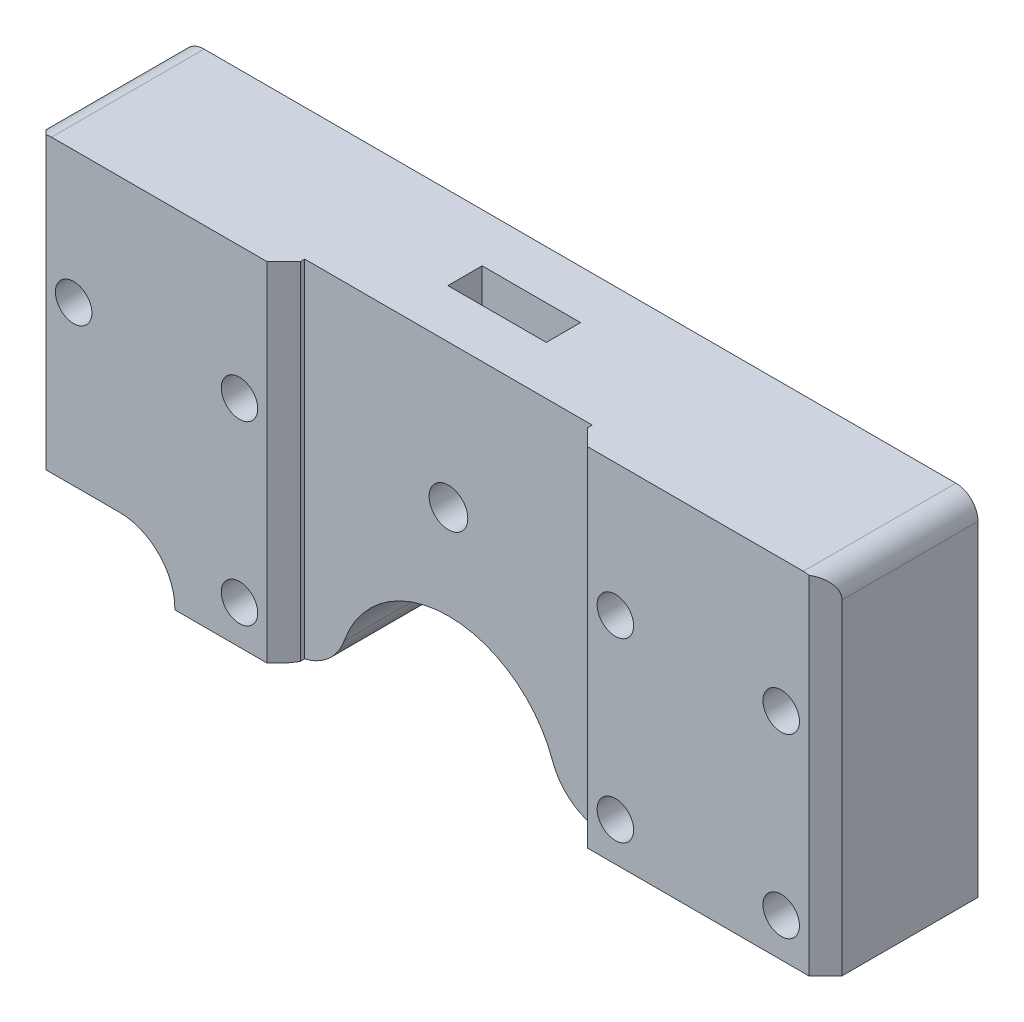
SolidWorks part; units mm, degrees
ref_plane "Alzado" through (0, 0, 0) normal (0, 0, 1) x (1, 0, 0)
ref_plane "Planta" through (0, 0, 0) normal (0, 1, 0) x (1, 0, 0)
ref_plane "Vista lateral" through (0, 0, 0) normal (1, 0, 0) x (0, 0, -1)
sketch "Croquis1" plane through (0, 0, 0) normal (0, 1, 0) x (1, 0, 0)
  line L1 (0, 0) -> (72, 0)
  line L2 (0, 0) -> (0, 35.8)
  line L3 (0, 35.8) -> (72, 35.8)
  line L4 (72, 0) -> (72, 35.8)
  dimension "D1" = 72
  dimension "D2" = 35.8
extrude "Saliente-Extruir1" add sketch "Croquis1" along normal blind 23
sketch "Croquis2" plane through (0, 0, -35.8) normal (0, 0, -1) x (-1, 0, 0)
  line L0 (-36, 23) -> (-36, 0) construction
  line L1 (-72, 23) -> (0, 23) construction
  line L2 (-72, 0) -> (0, 0) construction
  line L3 (-69.4, 20) -> (-47, 20)
  line L4 (-69.4, 20) -> (-69.4, -5)
  line L5 (-2.6, 20) -> (-2.6, -5)
  line L6 (-2.6, -5) -> (-69.4, -5)
  line L7 (-25, 20) -> (-2.6, 20)
  line L8 (-47, 23) -> (-25, 23)
  line L9 (-47, 23) -> (-47, 20)
  line L11 (-25, 23) -> (-25, 20)
  point P16 (-36, 23)
  dimension "D1" = 3
  dimension "D2" = 66.8
  dimension "D3" = 25
  dimension "D4" = 22
  dimension "D5" = 22.4
extrude "Cortar-Extruir2" cut sketch "Croquis2" against normal blind 2.8
sketch "Croquis3" plane through (0, 23, 0) normal (0, 1, 0) x (1, 0, 0)
  line L0 (36, 33) -> (36, 0) construction
  line L1 (25, 33) -> (47, 33) construction
  line L2 (0, 0) -> (72, 0) construction
  line L3 (72, 35.8) -> (47, 35.8) construction
  line L4 (33.05, 31.4) -> (38.95, 31.4)
  line L5 (33.05, 31.4) -> (33.05, 28.3)
  line L6 (33.05, 28.3) -> (38.95, 28.3)
  line L7 (38.95, 31.4) -> (38.95, 28.3)
  point P10 (36, 28.3)
  dimension "D1" = 4.4
  dimension "D2" = 3.1
  dimension "D3" = 5.9
extrude "Cortar-Extruir3" cut sketch "Croquis3" against normal blind 7.91
sketch "Croquis4" plane through (0, 0, -28.3) normal (0, 0, -1) x (-1, 0, 0)
  line L0 (-36, 23) -> (-36, 15.09) construction
  line L1 (-33.05, 23) -> (-38.95, 23) construction
  line L2 (-33.05, 15.09) -> (-38.95, 15.09) construction
  line L3 (-38.95, 16.7932) -> (-38.95, 15.09)
  line L4 (-36, 15.09) -> (-33.05, 16.7932)
  line L5 (-33.05, 16.7932) -> (-33.05, 20.1995) construction
  line L6 (-33.05, 20.1995) -> (-36, 21.9027) construction
  line L7 (-36, 21.9027) -> (-38.95, 20.1995) construction
  line L8 (-38.95, 20.1995) -> (-38.95, 16.7932) construction
  line L9 (-38.95, 16.7932) -> (-36, 15.09)
  line L10 (-38.95, 15.09) -> (-36, 15.09)
  line L11 (-36, 15.09) -> (-33.05, 15.09)
  line L12 (-33.05, 15.09) -> (-33.05, 16.7932)
  circle A0 centre (-36, 18.4964) radius 2.95 construction
  line M6 (-38.95, 23) -> (-38.95, 15.09)
  line M7 (-38.95, 15.09) -> (-33.05, 15.09)
  line M8 (-33.05, 15.09) -> (-33.05, 23)
extrude "Saliente-Extruir3" add sketch "Croquis4" along normal up to surface (3.1 mm away) contours L4 M7 M8 | L9 M6 M7 up to face at (36, 19.045, -31.4)
sketch "Croquis7" plane through (0, 23, 0) normal (0, 1, 0) x (1, 0, 0)
  line L0 (72, 0) -> (72, 35.8) construction
  line L1 (0, 0) -> (72, 0)
  line L2 (0, 0) -> (0, 22)
  line L3 (0, 22) -> (72, 22)
  line L4 (72, 0) -> (72, 22)
  dimension "D1" = 22
extrude "Cortar-Extruir6" cut sketch "Croquis7" against normal blind 37.91
sketch "Croquis9" plane through (0, 0, -28.3) normal (0, 0, -1) x (-1, 0, 0)
  line L0 (-36, 23) -> (-36, 15.09) construction
  line L1 (-33.05, 23) -> (-38.95, 23) construction
  line L2 (-33.05, 16.7932) -> (-33.05, 23) construction
  line L3 (-36, 15.09) -> (-33.05, 16.7932) construction
  line L4 (-33.05, 16.7932) -> (-33.05, 20.1995) construction
  line L5 (-33.05, 20.1995) -> (-36, 21.9027) construction
  line L6 (-36, 21.9027) -> (-38.95, 20.1995) construction
  line L7 (-38.95, 20.1995) -> (-38.95, 16.7932) construction
  line L8 (-38.95, 16.7932) -> (-36, 15.09) construction
  circle A0 centre (-36, 18.4964) radius 2.95 construction
  circle A1 centre (-36, 18.4964) radius 1.75
  dimension "D1" = 3.5
extrude "Cortar-Extruir8" cut sketch "Croquis9" against normal blind 15 and the other way blind 15
sketch "Croquis11" plane through (0, 0, -33) normal (0, 0, -1) x (-1, 0, 0)
  line L0 (-36, 23) -> (-36, 0) construction
  line L1 (-25, 23) -> (-47, 23) construction
  line L2 (-69.4, 0) -> (-2.6, 0) construction
  circle A0 centre (-36, 0) radius 10
  dimension "D1" = 20
extrude "Cortar-Extruir10" cut sketch "Croquis11" against normal blind 10
fillet "Redondeo1" radius 5 2 edges at (26, 0, -28) (46, 0, -28)
sketch "Croquis12" plane through (0, 23, 0) normal (0, 1, 0) x (1, 0, 0)
  line L16 (0, 35.8) -> (0, 22)
  line L17 (0, 22) -> (72, 22)
  line L18 (72, 22) -> (72, 35.8)
  line L19 (72, 35.8) -> (47, 35.8)
  line L20 (47, 35.8) -> (47, 33)
  line L21 (47, 33) -> (25, 33)
  line L22 (25, 33) -> (25, 35.8)
  line L23 (25, 35.8) -> (0, 35.8)
  line L24 (0, 35.8) -> (0, 22)
  line L25 (0, 22) -> (72, 22)
  line L26 (72, 22) -> (72, 35.8)
  line L27 (72, 35.8) -> (0, 35.8)
  line L43 (33.05, 28.3) -> (38.95, 28.3)
  line L44 (38.95, 28.3) -> (38.95, 31.4)
  line L45 (38.95, 31.4) -> (33.05, 31.4)
  line L46 (33.05, 31.4) -> (33.05, 28.3)
  line L47 (33.05, 28.3) -> (38.95, 28.3)
  line L48 (38.95, 28.3) -> (38.95, 31.4)
  line L49 (38.95, 31.4) -> (33.05, 31.4)
  line L50 (33.05, 31.4) -> (33.05, 28.3)
  dimension "D1" = 0
  dimension "D2" = 0
extrude "Saliente-Extruir4" add sketch "Croquis12" along normal blind 3.5
sketch "Croquis13" plane through (0, 0, -22) normal (0, 0, 1) x (1, 0, 0)
  line L0 (36, 26.5) -> (36, 0) construction
  line L1 (4, 3.5) -> (19, 3.5) construction
  line L2 (4, 3.5) -> (4, 19.5) construction
  line L3 (4, 19.5) -> (19, 19.5) construction
  line L4 (19, 3.5) -> (19, 19.5) construction
  line L5 (0, 26.5) -> (72, 26.5) construction
  line L6 (0, 0) -> (72, 0) construction
  circle A0 centre (4, 3.5) radius 1.65 construction
  circle A1 centre (19, 3.5) radius 1.65
  circle A2 centre (19, 19.5) radius 1.65
  circle A3 centre (4, 19.5) radius 1.65
  circle A4 centre (53, 3.5) radius 1.65
  circle A5 centre (68, 3.5) radius 1.65
  circle A6 centre (68, 19.5) radius 1.65
  circle A7 centre (53, 19.5) radius 1.65
  dimension "D1" = 3.3
  dimension "D2" = 4
  dimension "D3" = 3.5
  dimension "D4" = 15
  dimension "D5" = 16
extrude "Cortar-Extruir11" cut sketch "Croquis13" against normal blind 33.5
sketch "Croquis14" plane through (0, 0, -33) normal (0, 0, -1) x (-1, 0, 0)
  circle A0 centre (-53, 19.5) radius 2.85
  circle A1 centre (-53, 3.5) radius 2.85
  circle A2 centre (-68, 3.5) radius 2.85
  circle A3 centre (-68, 19.5) radius 2.85
  circle A4 centre (-19, 3.5) radius 2.85
  circle A5 centre (-19, 19.5) radius 2.85
  circle A6 centre (-4, 19.5) radius 2.85
  dimension "D1" = 5.7
extrude "Cortar-Extruir12" cut sketch "Croquis14" against normal blind 3 and the other way blind 33.5
sketch "Croquis15" plane through (0, 26.5, 0) normal (0, 1, 0) x (1, 0, 0)
  line L0 (36, 35.8) -> (36, 22) construction
  line L1 (72, 35.8) -> (0, 35.8) construction
  line L2 (0, 22) -> (72, 22) construction
  line L4 (23, 23.9) -> (49, 23.9)
  line L5 (23, 23.9) -> (23, 22)
  line L6 (23, 22) -> (49, 22)
  line L7 (49, 23.9) -> (49, 22)
  point P10 (36, 22)
  dimension "D1" = 1.9
  dimension "D2" = 26
extrude "Cortar-Extruir13" cut sketch "Croquis15" against normal blind 43
chamfer "Chaflán1" distance 1.5 angle 45 4 edges at (49, 13.25, -22) (23, 13.25, -22) (72, 13.25, -22) (0, 13.25, -22)
chamfer "Chaflán2" distance 1.5 angle 45 2 edges at (38.95, 26.5, -29.85) (33.05, 26.5, -29.85)
sketch "Croquis16" plane through (0, 0, -35.8) normal (0, 0, -1) x (-1, 0, 0)
  line L1 (0, 0) -> (-13.15, 0)
  line L2 (0, 0) -> (0, 5.14)
  line L3 (0, 5.14) -> (-13.15, 5.14)
  line L4 (-13.15, 0) -> (-13.15, 5.14)
  dimension "D1" = 5.14
  dimension "D2" = 13.15
extrude "Cortar-Extruir14" cut sketch "Croquis16" against normal blind 20
fillet "Redondeo3" radius 5 1 edges at (13.15, 5.14, -27.5)
sketch "Croquis17" plane through (0, 26.5, 0) normal (0, 1, 0) x (1, 0, 0)
  line L24 (50.5, 22) -> (70.5, 22)
  line L25 (70.5, 22) -> (72, 23.5)
  line L26 (70.5, 22) -> (72, 23.5)
  line L27 (72, 35.8) -> (0, 35.8)
  line L28 (72, 23.5) -> (72, 35.8)
  line L29 (72, 23.5) -> (72, 35.8)
  line L30 (1.5, 22) -> (21.5, 22)
  line L31 (21.5, 22) -> (23, 23.5)
  line L32 (23, 23.5) -> (23, 23.9)
  line L33 (23, 23.9) -> (49, 23.9)
  line L34 (49, 23.9) -> (49, 23.5)
  line L35 (49, 23.5) -> (50.5, 22)
  line L36 (50.5, 22) -> (70.5, 22)
  line L39 (72, 35.8) -> (0, 35.8)
  line L42 (1.5, 22) -> (21.5, 22)
  line L43 (21.5, 22) -> (23, 23.5)
  line L44 (23, 23.5) -> (23, 23.9)
  line L45 (23, 23.9) -> (49, 23.9)
  line L46 (49, 23.9) -> (49, 23.5)
  line L47 (49, 23.5) -> (50.5, 22)
  line L50 (31.55, 31.4) -> (31.55, 28.3)
  line L51 (40.45, 31.4) -> (31.55, 31.4)
  line L52 (40.45, 28.3) -> (40.45, 31.4)
  line L53 (31.55, 28.3) -> (40.45, 28.3)
  line L54 (31.55, 31.4) -> (31.55, 28.3)
  line L55 (40.45, 31.4) -> (31.55, 31.4)
  line L56 (40.45, 28.3) -> (40.45, 31.4)
  line L57 (31.55, 28.3) -> (40.45, 28.3)
  line L62 (0, 35.8) -> (0, 23.5)
  line L63 (0, 35.8) -> (0, 23.5)
  line L64 (0, 23.5) -> (1.5, 22)
  line L65 (0, 23.5) -> (1.5, 22)
  dimension "D1" = 0
  dimension "D2" = 0
extrude "Saliente-Extruir5" add sketch "Croquis17" along normal blind 4.95
fillet "Redondeo4" radius 2 2 edges at (72, 31.45, -29.65) (0, 31.45, -29.65)
